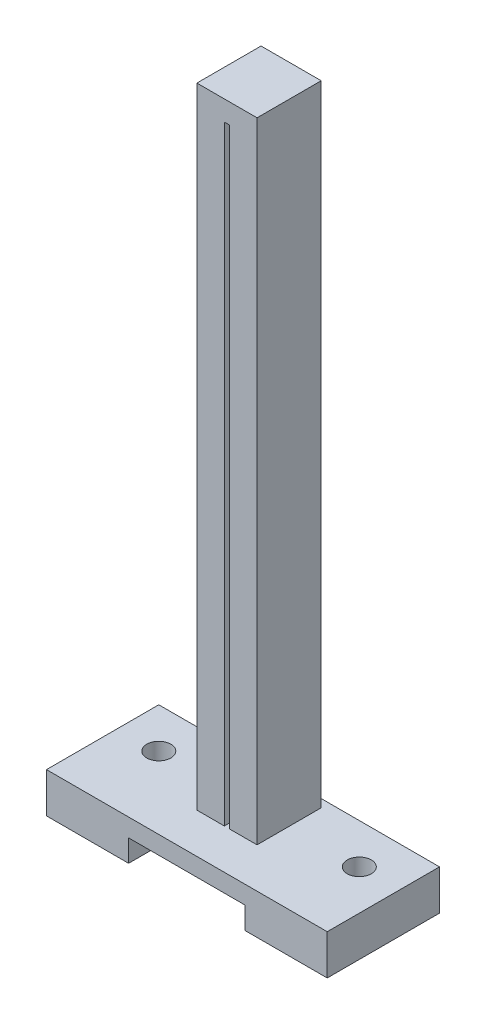
SolidWorks part; units mm, degrees
ref_plane "前基準面" through (0, 0, 0) normal (0, 0, 1) x (1, 0, 0)
ref_plane "上基準面" through (0, 0, 0) normal (0, 1, 0) x (1, 0, 0)
ref_plane "右基準面" through (0, 0, 0) normal (1, 0, 0) x (0, 0, -1)
sketch "草圖1" plane through (0, 0, 0) normal (0, 1, 0) x (1, 0, 0)
  line L1 (-35, 21.5) -> (35, 21.5)
  line L2 (-35, 21.5) -> (-35, -21.5)
  line L3 (-35, -21.5) -> (35, -21.5)
  line L4 (35, 21.5) -> (35, -21.5)
  line L5 (-35, 21.5) -> (35, -21.5) construction
  line L6 (-35, -21.5) -> (35, 21.5) construction
  point P0 (0, 0)
  dimension "D1" = 70
  dimension "D2" = 43
extrude "填料-伸長1" add sketch "草圖1" along normal blind 10
sketch "草圖21" plane through (0, 10, 0) normal (0, 1, 0) x (1, 0, 0)
  line L0 (35, 21.5) -> (-35, 21.5) construction
  line L1 (-35, 21.5) -> (-35, -21.5) construction
  circle A0 centre (-25, 11.5) radius 3
  dimension "D1" = 10
  dimension "D2" = 10
  dimension "D3" = 6
extrude "除料-伸長12" cut sketch "草圖21" against normal through all
sketch "草圖22" plane through (0, 10, 0) normal (0, 1, 0) x (1, 0, 0)
  line L0 (35, 21.5) -> (-35, 21.5) construction
  line L1 (35, -21.5) -> (35, 21.5) construction
  circle A0 centre (25, 11.5) radius 3
  dimension "D1" = 10
  dimension "D2" = 10
  dimension "D3" = 6
extrude "除料-伸長13" cut sketch "草圖22" against normal through all
sketch "草圖46" plane through (0, 10, 0) normal (0, 1, 0) x (1, 0, 0)
  line L0 (-1028, 11.5) -> (48972, 11.5) construction
  line L1 (0, -1000) -> (0, 49000) construction
  line L3 (-7.5, 17.5) -> (7.5, 17.5)
  line L4 (-7.5, 17.5) -> (-7.5, 5.5)
  line L5 (-7.5, 5.5) -> (7.5, 5.5)
  line L6 (7.5, 17.5) -> (7.5, 5.5)
  line L7 (-7.5, 17.5) -> (7.5, 5.5) construction
  line L8 (-7.5, 5.5) -> (7.5, 17.5) construction
  point P3 (0, 11.5)
  dimension "D1" = 15
  dimension "D2" = 12
extrude "填料-伸長4" add sketch "草圖46" along normal blind 200
sketch "草圖76" plane through (0, 0, -17.5) normal (0, 0, -1) x (-1, 0, 0)
  line L0 (0, -790) -> (0, 49210) construction
  line L1 (-7.5, 210) -> (7.5, 210) construction
  line L2 (-35, 10) -> (35, 10) construction
  line L3 (-3.825, 210) -> (3.825, 210)
  line L4 (-3.825, 210) -> (-3.825, 10)
  line L5 (-3.825, 10) -> (3.825, 10)
  line L6 (3.825, 210) -> (3.825, 10)
  line L7 (-3.825, 210) -> (3.825, 10) construction
  line L8 (-3.825, 10) -> (3.825, 210) construction
  point P1 (0, 110)
  point P5 (0, 210)
  dimension "D1" = 7.65
  dimension "D2" = 0
  dimension "D3" = 0
extrude "除料-伸長37" cut sketch "草圖76" against normal through all
sketch "草圖78" plane through (0, 10, 0) normal (0, 1, 0) x (1, 0, 0)
  line L1 (-7.5, 5.5) -> (7.5, 5.5)
  line L2 (-7.5, 5.5) -> (-7.5, 3.5)
  line L3 (-7.5, 3.5) -> (7.5, 3.5)
  line L4 (7.5, 5.5) -> (7.5, 3.5)
  dimension "D1" = 2
extrude "填料-伸長16" add sketch "草圖78" along normal blind 200
sketch "草圖79" plane through (0, 10, 0) normal (0, 1, 0) x (1, 0, 0)
  line L1 (-7.5, 17.5) -> (7.5, 17.5)
  line L2 (-7.5, 17.5) -> (-7.5, 19.5)
  line L3 (-7.5, 19.5) -> (7.5, 19.5)
  line L4 (7.5, 17.5) -> (7.5, 19.5)
  dimension "D1" = 2
extrude "填料-伸長17" add sketch "草圖79" along normal blind 200
sketch "草圖80" plane through (0, 0, -3.5) normal (0, 0, 1) x (1, 0, 0)
  line L0 (0, -790) -> (0, 49210) construction
  line L1 (-7.5, 210) -> (7.5, 210) construction
  line L2 (-7.5, 10) -> (7.5, 10) construction
  line L3 (-0.65, 210) -> (0.65, 210)
  line L4 (-0.65, 210) -> (-0.65, 10)
  line L5 (-0.65, 10) -> (0.65, 10)
  line L6 (0.65, 210) -> (0.65, 10)
  line L7 (-0.65, 210) -> (0.65, 10) construction
  line L8 (-0.65, 10) -> (0.65, 210) construction
  point P1 (0, 110)
  point P5 (0, 210)
  dimension "D1" = 1.3
  dimension "D2" = 0
  dimension "D3" = 0
extrude "除料-伸長38" cut sketch "草圖80" against normal through all
sketch "草圖82" plane through (0, 210, 0) normal (0, 1, 0) x (1, 0, 0)
  line L1 (-7.5, 19.5) -> (7.5, 19.5)
  line L2 (-7.5, 19.5) -> (-7.5, 3.5)
  line L3 (-7.5, 3.5) -> (7.5, 3.5)
  line L4 (7.5, 19.5) -> (7.5, 3.5)
sketch "草圖83" plane through (0, 10, 0) normal (0, 1, 0) x (1, 0, 0)
  line L1 (-3.825, 17.5) -> (3.825, 17.5)
  line L2 (-3.825, 17.5) -> (-3.825, 5.5)
  line L3 (-3.825, 5.5) -> (3.825, 5.5)
  line L4 (3.825, 17.5) -> (3.825, 5.5)
extrude "除料-伸長39" cut sketch "草圖83" against normal through all
sketch "草圖84" plane through (0, 0, -21.5) normal (0, 0, -1) x (-1, 0, 0)
  line L0 (0, 10) -> (0, 0) construction
  line L1 (-35, 10) -> (35, 10) construction
  line L3 (-5, 5.5) -> (5, 5.5)
  line L4 (-5, 5.5) -> (-5, -5.5)
  line L5 (-5, -5.5) -> (5, -5.5)
  line L6 (5, 5.5) -> (5, -5.5)
  line L7 (-5, 5.5) -> (5, -5.5) construction
  line L8 (-5, -5.5) -> (5, 5.5) construction
  dimension "D1" = 10
  dimension "D2" = 11
extrude "除料-伸長40" cut sketch "草圖84" against normal through all
extrude "填料-伸長19" add sketch "草圖82" along normal blind 10
sketch "草圖85" plane through (0, 10, 0) normal (0, 1, 0) x (1, 0, 0)
  line L0 (-35, 21.5) -> (-35, -21.5) construction
  line L1 (35, -21.5) -> (-35, -21.5)
  line L2 (35, -21.5) -> (35, -6.5)
  line L3 (35, -6.5) -> (-35, -6.5)
  line L4 (-35, -21.5) -> (-35, -6.5)
  dimension "D1" = 15
extrude "除料-伸長41" cut sketch "草圖85" against normal blind 10
sketch "草圖86" plane through (0, 0, -3.5) normal (0, 0, 1) x (1, 0, 0)
  line L0 (7.5, 220) -> (7.5, 10) construction
  line L1 (-7.5, 220) -> (7.5, 220)
  line L2 (-7.5, 220) -> (-7.5, 185)
  line L3 (-7.5, 185) -> (7.5, 185)
  line L4 (7.5, 220) -> (7.5, 185)
  dimension "D1" = 35
extrude "除料-伸長42" cut sketch "草圖86" against normal blind 25
sketch "草圖87" plane through (0, 185, 0) normal (0, 1, 0) x (1, 0, 0)
  line L1 (-7.5, 3.5) -> (7.5, 3.5)
  line L2 (-7.5, 3.5) -> (-7.5, 19.5)
  line L3 (-7.5, 19.5) -> (7.5, 19.5)
  line L4 (7.5, 3.5) -> (7.5, 19.5)
extrude "填料-伸長20" add sketch "草圖87" along normal blind 5
sketch "草圖88" plane through (0, 0, -19.5) normal (0, 0, -1) x (-1, 0, 0)
  line L0 (-7.5, 190) -> (-7.5, 10) construction
  line L1 (7.5, 190) -> (-7.5, 190)
  line L2 (7.5, 190) -> (7.5, 162)
  line L3 (7.5, 162) -> (-7.5, 162)
  line L4 (-7.5, 190) -> (-7.5, 162)
  dimension "D1" = 28
extrude "除料-伸長43" cut sketch "草圖88" against normal blind 35
sketch "草圖89" plane through (0, 162, 0) normal (0, 1, 0) x (1, 0, 0)
  line L1 (-7.5, 3.5) -> (7.5, 3.5)
  line L2 (-7.5, 3.5) -> (-7.5, 19.5)
  line L3 (-7.5, 19.5) -> (7.5, 19.5)
  line L4 (7.5, 3.5) -> (7.5, 19.5)
extrude "填料-伸長21" add sketch "草圖89" along normal blind 5
sketch "草圖90" plane through (0, 0, 6.5) normal (0, 0, 1) x (1, 0, 0)
  line L0 (0, -994.5) -> (0, 49005.5) construction
  line L1 (5, 5.5) -> (-5, 5.5) construction
  line L3 (-14.5226, 5.5) -> (14.5226, 5.5)
  line L4 (-14.5226, 5.5) -> (-14.5226, -5.5)
  line L5 (-14.5226, -5.5) -> (14.5226, -5.5)
  line L6 (14.5226, 5.5) -> (14.5226, -5.5)
  line L7 (-14.5226, 5.5) -> (14.5226, -5.5) construction
  line L8 (-14.5226, -5.5) -> (14.5226, 5.5) construction
  point P1 (0, 0)
  point P5 (0, 5.5)
  dimension "D1" = 0
extrude "除料-伸長44" cut sketch "草圖90" against normal blind 20
